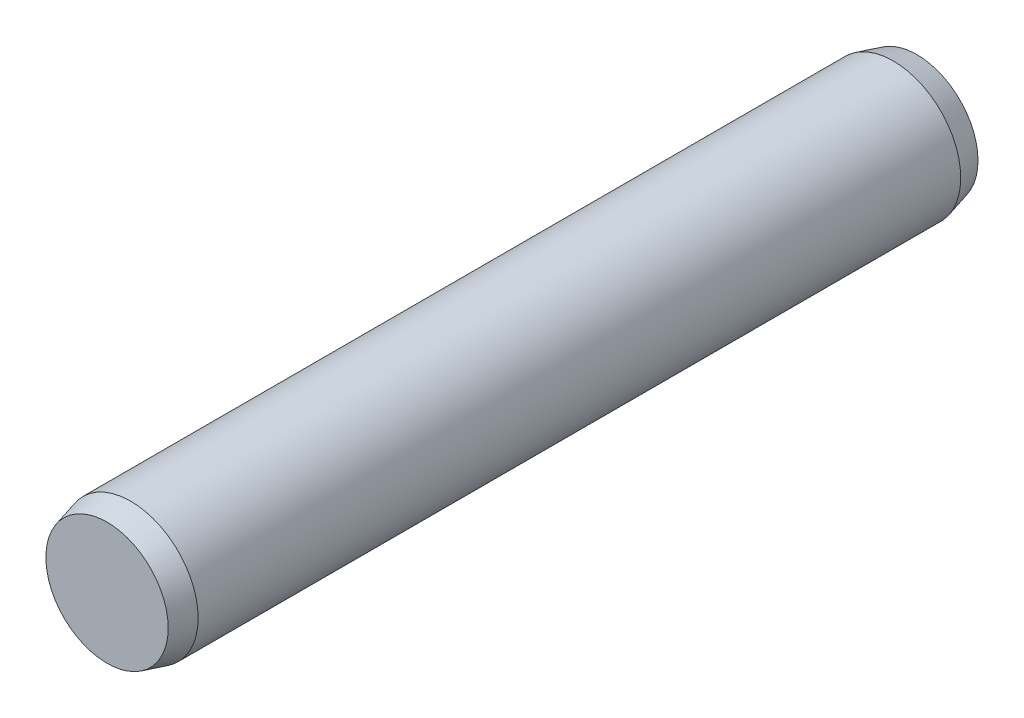
SolidWorks part; units mm, degrees
ref_plane "Front Plane" through (0, 0, 0) normal (0, 0, 1) x (1, 0, 0)
ref_plane "Top Plane" through (0, 0, 0) normal (0, 1, 0) x (1, 0, 0)
ref_plane "Right Plane" through (0, 0, 0) normal (1, 0, 0) x (0, 0, -1)
sketch "Sketch1" plane through (0, 0, 0) normal (1, 0, 0) x (0, 0, -1)
  line L0 (-6, 0) -> (6, 0)
  dimension "Length" = 12
sketch "Sketch2" plane through (0, 0, 0) normal (0, 0, 1) x (1, 0, 0)
  circle A0 centre (0, 0) radius 1
  dimension "Diameter" = 2
sketch "Sketch3" plane through (0, 0, 0) normal (1, 0, 0) x (0, 0, -1)
  line L0 (-6, 0) -> (-6, 0.9062)
  line L1 (-6, 0.9062) -> (-5.65, 1)
  line L2 (-5.65, 1) -> (5.65, 1)
  line L5 (6, 0) -> (-6, 0)
  line L6 (-6, 0) -> (6, 0) construction
  line L7 (-6, 0) -> (6, 0) construction
  line L8 (5.65, 1) -> (6, 0.9062)
  line L9 (6, 0.9062) -> (6, 0)
  point P0 (0, 1)
  dimension "D1" = 15
  dimension "Point Height" = 0.35
revolve "Revolve1" add sketch "Sketch3" angle 360 about L0
